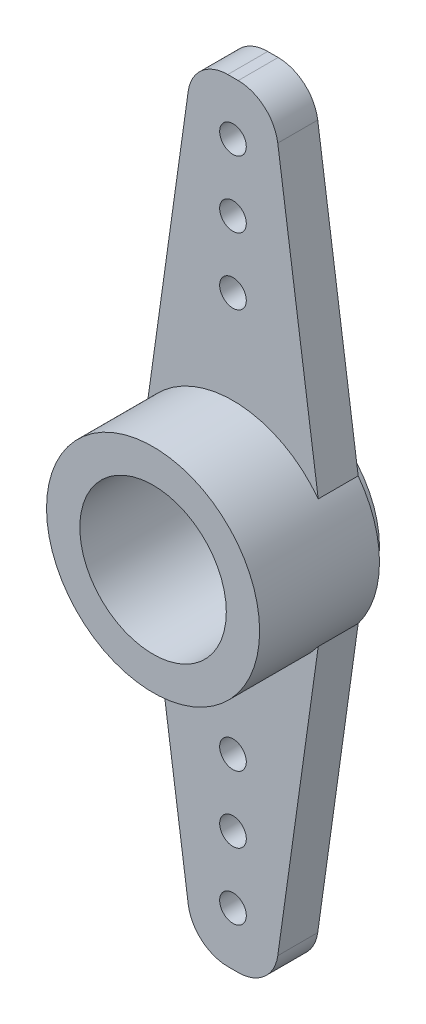
SolidWorks part; units mm, degrees
ref_plane "Front" through (0, 0, 0) normal (0, 0, 1) x (1, 0, 0)
ref_plane "Top" through (0, 0, 0) normal (0, 1, 0) x (1, 0, 0)
ref_plane "Right" through (0, 0, 0) normal (1, 0, 0) x (0, 0, -1)
sketch "Sketch1" plane through (0, 0, 0) normal (0, 0, 1) x (1, 0, 0)
  line L0 (0, 0) -> (0, 33.5454) construction
  line L1 (-0.196, 14.5) -> (0.196, 14.5) construction
  line L2 (-3.2, 2.4) -> (-1.6814, 13.2087)
  line L3 (3.2, 2.4) -> (1.6814, 13.2087)
  line L4 (-0.196, 14.5) -> (0.196, 14.5)
  line L5 (-4, 0) -> (4, 0) construction
  line L6 (-0.196, -14.5) -> (0.196, -14.5) construction
  line L7 (-0.196, -14.5) -> (0.196, -14.5)
  line L8 (3.2, -2.4) -> (1.6814, -13.2087)
  line L9 (-3.2, -2.4) -> (-1.6814, -13.2087)
  arc A0 (-3.2, 2.4) -> (-3.2, -2.4) centre (0, 0) ccw
  circle A1 centre (0, 10) radius 0.5
  circle A2 centre (0, 12.5) radius 0.5
  circle A3 centre (0, 7.5) radius 0.5
  arc A4 (1.6814, 13.2087) -> (0.196, 14.5) centre (0.196, 13) ccw
  arc A5 (-0.196, 14.5) -> (-1.6814, 13.2087) centre (-0.196, 13) ccw
  circle A6 centre (0, 0) radius 1.5
  arc A7 (-0.196, -14.5) -> (-1.6814, -13.2087) centre (-0.196, -13) cw
  arc A8 (1.6814, -13.2087) -> (0.196, -14.5) centre (0.196, -13) cw
  circle A9 centre (0, -7.5) radius 0.5
  circle A10 centre (0, -12.5) radius 0.5
  circle A11 centre (0, -10) radius 0.5
  arc A12 (3.2, -2.4) -> (3.2, 2.4) centre (0, 0) ccw
  dimension "D1" = 8
  dimension "D3" = 1
  dimension "D5" = 1
  dimension "D6" = 1
  dimension "D11" = 1.5
  dimension "D9" = 1.5
  dimension "D12" = 3
  dimension "D2" = 14.5
  dimension "D4" = 10
  dimension "D7" = 2.5
  dimension "D8" = 2.5
  dimension "D10" = 3.2
extrude "Boss-Extrude3" add sketch "Sketch1" along normal blind 1.5
sketch "Sketch2" plane through (0, 0, 1.5) normal (0, 0, 1) x (1, 0, 0)
  circle A0 centre (0, 0) radius 4
extrude "Boss-Extrude4" add sketch "Sketch2" along normal blind 3
sketch "Sketch3" plane through (0, 0, 0) normal (0, 0, -1) x (-1, 0, 0)
  circle A0 centre (0, 0) radius 3.5
  circle A4 centre (0, 0) radius 3.25
  dimension "D1" = 7
  dimension "D2" = 0.25
extrude "Boss-Extrude5" add sketch "Sketch3" along normal blind 0.5
sketch "Sketch4" plane through (0, 0, 4.5) normal (0, 0, 1) x (1, 0, 0)
  circle A0 centre (0, 0) radius 2.75
  dimension "D1" = 5.5
extrude "Cut-Extrude1" cut sketch "Sketch4" against normal blind 4
